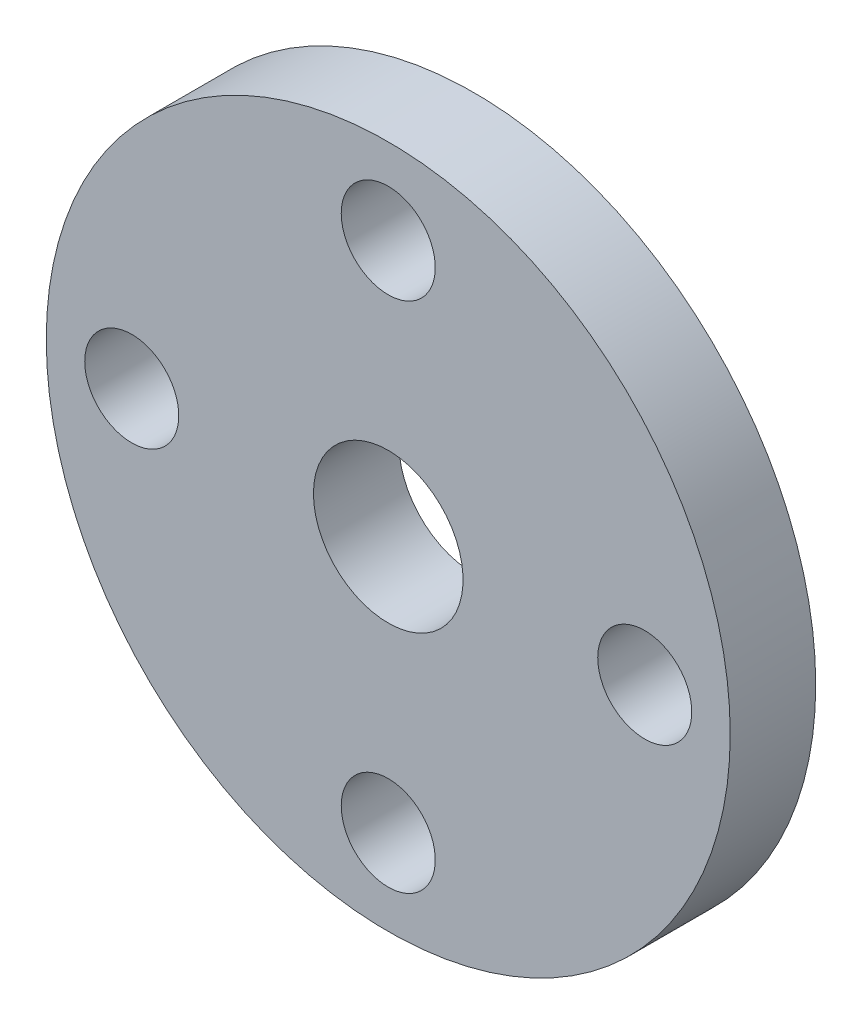
SolidWorks part; units mm, degrees
ref_plane "前视基准面" through (0, 0, 0) normal (0, 0, 1) x (1, 0, 0)
ref_plane "上视基准面" through (0, 0, 0) normal (0, 1, 0) x (1, 0, 0)
ref_plane "右视基准面" through (0, 0, 0) normal (1, 0, 0) x (0, 0, -1)
sketch "草图2" plane through (0, 0, 0) normal (0, 0, 1) x (1, 0, 0)
  line L0 (-24.0911, 0) -> (29.1181, 0) construction
  line L1 (0, 19.0917) -> (0, -19.7619) construction
sketch "草图1" plane through (0, 0, 0) normal (0, 0, 1) x (1, 0, 0)
  circle A0 centre (0, 0) radius 8
  dimension "D1" = 16
extrude "凸台-拉伸1" add sketch "草图1" along normal blind 2
sketch "草图3" plane through (0, 0, 0) normal (0, 0, -1) x (-1, 0, 0)
  line L0 (0, 19.0917) -> (0, -19.7619) construction
  line L1 (24.0911, 0) -> (-29.1181, 0) construction
  circle A0 centre (0, 6) radius 1.1
  circle A1 centre (6, 0) radius 1.1
  circle A2 centre (0, -6) radius 1.1
  circle A3 centre (-6, 0) radius 1.1
  circle A4 centre (0, 0) radius 1.75
  dimension "D1" = 2.2
  dimension "D2" = 6
  dimension "D3" = 6
  dimension "D4" = 6
  dimension "D5" = 6
  dimension "D6" = 3.5
extrude "切除-拉伸1" cut sketch "草图3" against normal through all
